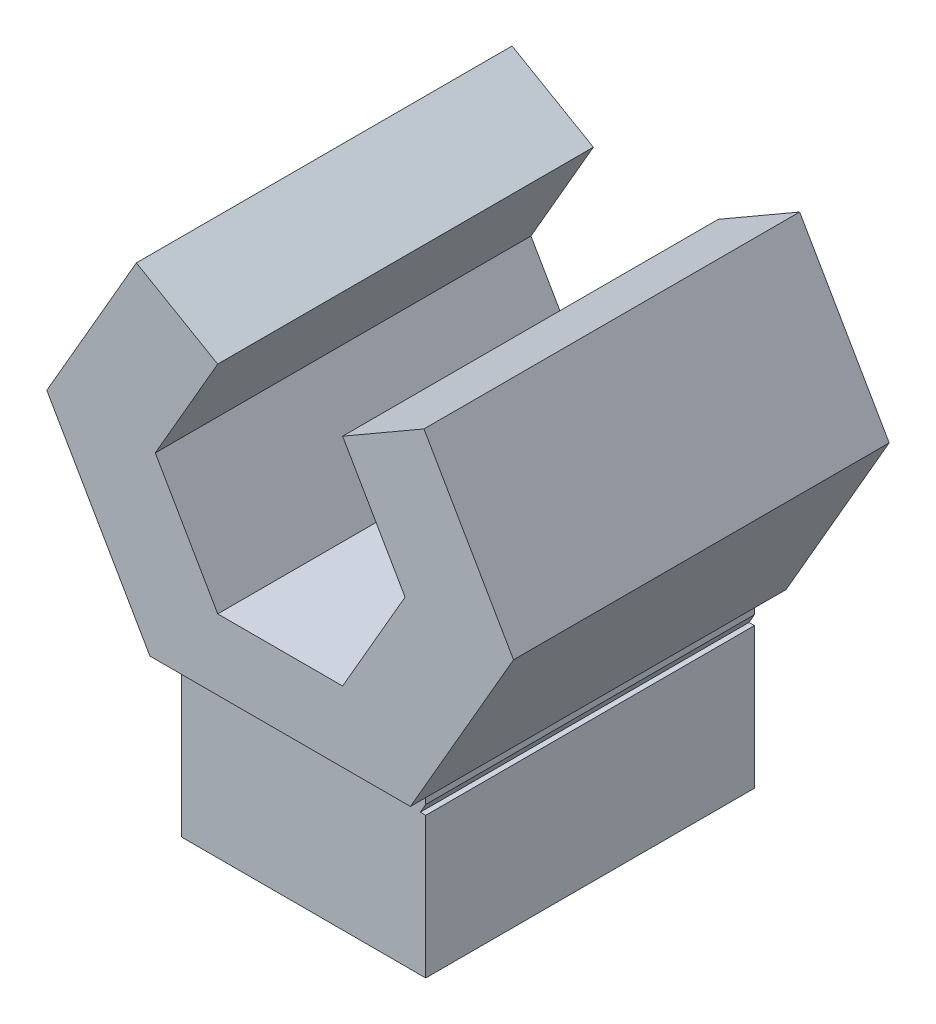
SolidWorks part; units mm, degrees
ref_plane "前视基准面" through (0, 0, 0) normal (0, 0, 1) x (1, 0, 0)
ref_plane "上视基准面" through (0, 0, 0) normal (0, 1, 0) x (1, 0, 0)
ref_plane "右视基准面" through (0, 0, 0) normal (1, 0, 0) x (0, 0, -1)
sketch "草图1" plane through (0, 0, 0) normal (0, 0, 1) x (1, 0, 0)
  line L0 (-2.66, 0) -> (-1.33, 2.3036) construction
  line L2 (1.33, 2.3036) -> (2.66, 0) construction
  line L3 (2.66, 0) -> (1.33, -2.3036) construction
  line L4 (1.33, -2.3036) -> (-1.33, -2.3036) construction
  line L5 (-1.33, -2.3036) -> (-2.66, 0) construction
  line L6 (-2.66, 0) -> (2.66, 0) construction
  line L13 (-3.0621, 3.3036) -> (-4.9694, 0)
  line L14 (-4.9694, 0) -> (-2.4847, -4.3036)
  line L15 (-2.4847, -4.3036) -> (2.4847, -4.3036)
  line L16 (2.4847, -4.3036) -> (4.9694, 0)
  line L19 (-1.33, 2.3036) -> (-2.66, 0)
  line L20 (-2.66, 0) -> (-1.33, -2.3036)
  line L21 (-1.33, -2.3036) -> (1.33, -2.3036)
  line L22 (1.33, -2.3036) -> (2.66, 0)
  line L23 (2.66, 0) -> (1.33, 2.3036)
  line L24 (4.9694, 0) -> (3.0621, 3.3036)
  line L25 (-3.0621, 3.3036) -> (-1.33, 2.3036)
  line L26 (1.33, 2.3036) -> (3.0621, 3.3036)
  point P2 (0, 0)
  dimension "D1" = 2.66
  dimension "D2" = 2
extrude "凸台-拉伸1" add sketch "草图1" along normal blind 8
sketch "草图2" plane through (0, -4.3036, 0) normal (0, -1, 0) x (1, 0, 0)
  line L0 (-4.9694, 8) -> (-2.4847, 8) construction
  line L1 (-4.5, 8) -> (4.5, 8)
  line L2 (-4.5, 8) -> (-4.5, 0)
  line L3 (-4.5, 0) -> (4.5, 0)
  line L4 (4.5, 8) -> (4.5, 0)
  line L5 (2.4847, 0) -> (4.9694, 0) construction
  dimension "D1" = 9
  dimension "D2" = 4.5
extrude "凸台-拉伸2" add sketch "草图2" along normal blind 3
sketch "草图3" plane through (0, -7.3036, 0) normal (0, -1, 0) x (1, 0, 0)
  line L0 (-4.5, 8) -> (4.5, 0) construction
  line L1 (4.5, 8) -> (-4.5, 0) construction
  line L3 (-1, 6.5) -> (1, 6.5)
  line L12 (-1, 6.5) -> (-1, 1.5)
  line L13 (-1, 1.5) -> (1, 1.5)
  line L14 (1, 6.5) -> (1, 1.5)
  line L15 (-1, 6.5) -> (1, 1.5) construction
  line L16 (-1, 1.5) -> (1, 6.5) construction
  line L17 (-2.6, 7.5) -> (2.6, 7.5)
  line L18 (-2.6, 7.5) -> (-2.6, 0.5)
  line L19 (-2.6, 0.5) -> (2.6, 0.5)
  line L20 (2.6, 7.5) -> (2.6, 0.5)
  line L21 (-2.6, 7.5) -> (2.6, 0.5) construction
  line L22 (-2.6, 0.5) -> (2.6, 7.5) construction
  point P2 (0, 4)
  point P4 (0, 4)
  point P11 (0, 4)
  dimension "D2" = 5
  dimension "D3" = 2
  dimension "D4" = 5.2
  dimension "D5" = 7
extrude "切除-拉伸1" cut sketch "草图3" against normal blind 3.5 flip side to cut
